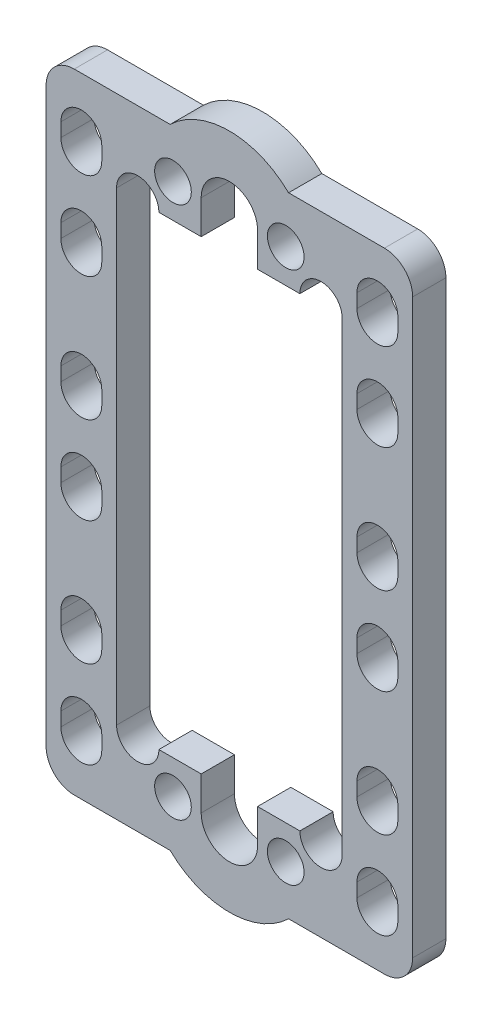
SolidWorks part; units mm, degrees
ref_plane "Front Plane" through (0, 0, 0) normal (0, 0, 1) x (1, 0, 0)
ref_plane "Top Plane" through (0, 0, 0) normal (0, 1, 0) x (1, 0, 0)
ref_plane "Right Plane" through (0, 0, 0) normal (1, 0, 0) x (0, 0, -1)
sketch "Sketch1" plane through (0, 0, 0) normal (0, 0, 1) x (1, 0, 0)
  line L0 (-11.7727, 30.48) -> (9.0183, 30.48) construction
  line L1 (16.51, 28.321) -> (5.334, 28.321)
  line L2 (16.51, 28.321) -> (16.51, -28.321)
  line L3 (16.51, -28.321) -> (5.334, -28.321)
  line L4 (-16.51, 28.321) -> (-16.51, -28.321)
  line L5 (16.51, 28.321) -> (-16.51, -28.321) construction
  line L6 (16.51, -28.321) -> (-16.51, 28.321) construction
  line L7 (10.16, 20.955) -> (-10.16, 20.955)
  line L8 (10.16, 20.955) -> (10.16, -20.955)
  line L9 (10.16, -20.955) -> (-10.16, -20.955)
  line L10 (-10.16, 20.955) -> (-10.16, -20.955)
  line L11 (10.16, 20.955) -> (-10.16, -20.955) construction
  line L12 (10.16, -20.955) -> (-10.16, 20.955) construction
  line L13 (-6.8859, -30.48) -> (11.7727, -30.48) construction
  line L14 (-5.334, 28.321) -> (-16.51, 28.321)
  line L15 (-5.334, -28.321) -> (-16.51, -28.321)
  arc A0 (-5.334, 28.321) -> (5.334, 28.321) centre (0, 22.8114) cw
  arc A1 (-5.334, -28.321) -> (5.334, -28.321) centre (0, -22.8114) ccw
  point P0 (0, 0)
  point P6 (0, 0)
  dimension "D1" = 56.642
  dimension "D2" = 33.02
  dimension "D3" = 20.32
  dimension "D4" = 41.91
  dimension "D5" = 60.96
  dimension "D6" = 11.176
extrude "Boss-Extrude1" add sketch "Sketch1" along normal blind 2.9972
sketch "Sketch2" plane through (0, 0, 2.9972) normal (0, 0, 1) x (1, 0, 0)
  line L0 (10.16, 20.955) -> (-10.16, 20.955) construction
  line L1 (5.08, 24) -> (-5.08, 24) construction
  line L2 (5.08, 24) -> (5.08, -24) construction
  line L3 (5.08, -24) -> (-5.08, -24) construction
  line L4 (-5.08, 24) -> (-5.08, -24) construction
  line L5 (5.08, 24) -> (-5.08, -24) construction
  line L6 (5.08, -24) -> (-5.08, 24) construction
  line L7 (-10.16, -20.955) -> (10.16, -20.955) construction
  line L8 (-10.16, 20.955) -> (-10.16, -20.955) construction
  line L9 (10.16, -20.955) -> (10.16, 20.955) construction
  line L10 (-6.35, 20.955) -> (-6.35, -20.955)
  line L11 (6.35, 20.955) -> (6.35, -20.955)
  line L12 (-10.16, 20.955) -> (-10.16, -20.955)
  line L13 (10.16, -20.955) -> (10.16, 20.955)
  line L14 (0, -24) -> (0, 24) construction
  line L15 (-2.54, -24) -> (-2.54, 24)
  line L16 (2.54, -24) -> (2.54, 24)
  circle A0 centre (-5.08, 24) radius 1.651
  circle A1 centre (5.08, 24) radius 1.651
  circle A2 centre (5.08, -24) radius 1.651
  circle A3 centre (-5.08, -24) radius 1.651
  arc A4 (-10.16, 20.955) -> (-6.35, 20.955) centre (-8.255, 20.955) cw
  arc A5 (10.16, 20.955) -> (6.35, 20.955) centre (8.255, 20.955) ccw
  arc A6 (-10.16, -20.955) -> (-6.35, -20.955) centre (-8.255, -20.955) ccw
  arc A7 (10.16, -20.955) -> (6.35, -20.955) centre (8.255, -20.955) cw
  arc A8 (-2.54, -24) -> (2.54, -24) centre (0, -24) ccw
  arc A9 (2.54, 24) -> (-2.54, 24) centre (0, 24) ccw
  point P0 (0, 0)
  point P32 (0, 0)
  dimension "D3" = 3.302
  dimension "D4" = 1.905
  dimension "D5" = 2.54
  dimension "D1" = 48
  dimension "D2" = 10.16
extrude "Cut-Extrude1" cut sketch "Sketch2" against normal through all
sketch "Sketch3" plane through (0, 0, 2.9972) normal (0, 0, 1) x (1, 0, 0)
  line L0 (-13.335, -28.321) -> (-13.335, 28.321) construction
  line L1 (-16.51, -28.321) -> (-5.334, -28.321) construction
  line L2 (-5.334, 28.321) -> (-16.51, 28.321) construction
  line L3 (-16.51, 0) -> (-13.335, 0) construction
  line L4 (-16.51, 28.321) -> (-16.51, -28.321) construction
  line L5 (-13.335, 0) -> (-10.16, 0) construction
  line L6 (-10.16, 20.955) -> (-10.16, -20.955) construction
  line L7 (-13.335, 23.6044) -> (-13.335, 22.3696) construction
  line L8 (-11.4935, 23.6044) -> (-11.4935, 22.3696)
  line L9 (-15.1765, 23.6044) -> (-15.1765, 22.3696)
  line L10 (-13.335, 15.7304) -> (-13.335, 14.4956) construction
  line L11 (-11.4935, 15.7304) -> (-11.4935, 14.4956)
  line L12 (-15.1765, 15.7304) -> (-15.1765, 14.4956)
  line L13 (-13.335, 4.5544) -> (-13.335, 3.3196) construction
  line L14 (-11.4935, 4.5544) -> (-11.4935, 3.3196)
  line L15 (-15.1765, 4.5544) -> (-15.1765, 3.3196)
  line L16 (-13.335, -3.3196) -> (-13.335, -4.5544) construction
  line L17 (-11.4935, -3.3196) -> (-11.4935, -4.5544)
  line L18 (-15.1765, -3.3196) -> (-15.1765, -4.5544)
  line L19 (-13.335, -14.4956) -> (-13.335, -15.7304) construction
  line L20 (-11.4935, -14.4956) -> (-11.4935, -15.7304)
  line L21 (-15.1765, -14.4956) -> (-15.1765, -15.7304)
  line L22 (-13.335, -22.3696) -> (-13.335, -23.6044) construction
  line L23 (-11.4935, -22.3696) -> (-11.4935, -23.6044)
  line L24 (-15.1765, -22.3696) -> (-15.1765, -23.6044)
  line L25 (-15.1765, 22.987) -> (-15.1765, 15.113) construction
  line L26 (-15.1765, 3.937) -> (-15.1765, -3.937) construction
  line L27 (-15.1765, -15.113) -> (-15.1765, -22.987) construction
  line L28 (-11.4935, 22.3696) -> (-11.4935, 3.3196) construction
  line L29 (-11.4935, -3.3196) -> (-11.4935, -22.3696) construction
  arc A0 (-11.4935, 23.6044) -> (-15.1765, 23.6044) centre (-13.335, 23.6044) ccw
  arc A1 (-15.1765, 22.3696) -> (-11.4935, 22.3696) centre (-13.335, 22.3696) ccw
  arc A2 (-11.4935, 15.7304) -> (-15.1765, 15.7304) centre (-13.335, 15.7304) ccw
  arc A3 (-15.1765, 14.4956) -> (-11.4935, 14.4956) centre (-13.335, 14.4956) ccw
  arc A4 (-11.4935, 4.5544) -> (-15.1765, 4.5544) centre (-13.335, 4.5544) ccw
  arc A5 (-15.1765, 3.3196) -> (-11.4935, 3.3196) centre (-13.335, 3.3196) ccw
  arc A6 (-11.4935, -3.3196) -> (-15.1765, -3.3196) centre (-13.335, -3.3196) ccw
  arc A7 (-15.1765, -4.5544) -> (-11.4935, -4.5544) centre (-13.335, -4.5544) ccw
  arc A8 (-11.4935, -14.4956) -> (-15.1765, -14.4956) centre (-13.335, -14.4956) ccw
  arc A9 (-15.1765, -15.7304) -> (-11.4935, -15.7304) centre (-13.335, -15.7304) ccw
  arc A10 (-11.4935, -22.3696) -> (-15.1765, -22.3696) centre (-13.335, -22.3696) ccw
  arc A11 (-15.1765, -23.6044) -> (-11.4935, -23.6044) centre (-13.335, -23.6044) ccw
  point P15 (-13.335, 22.987)
  point P20 (-13.335, 15.113)
  point P27 (-13.335, 3.937)
  point P34 (-13.335, -3.937)
  point P41 (-13.335, -15.113)
  point P48 (-13.335, -22.987)
  point P59 (-15.1765, 0)
  dimension "D1" = 7.874
  dimension "D2" = 19.05
  dimension "D3" = 3.683
extrude "Cut-Extrude2" cut sketch "Sketch3" against normal through all
mirror "Mirror1" about plane through (0, 0, 0) normal (1, 0, 0) of "Cut-Extrude2"
fillet "Fillet1" radius 2.54 4 edges at (-16.51, -28.321, 1.4986) (16.51, -28.321, 1.4986) (16.51, 28.321, 1.4986) (-16.51, 28.321, 1.4986)
